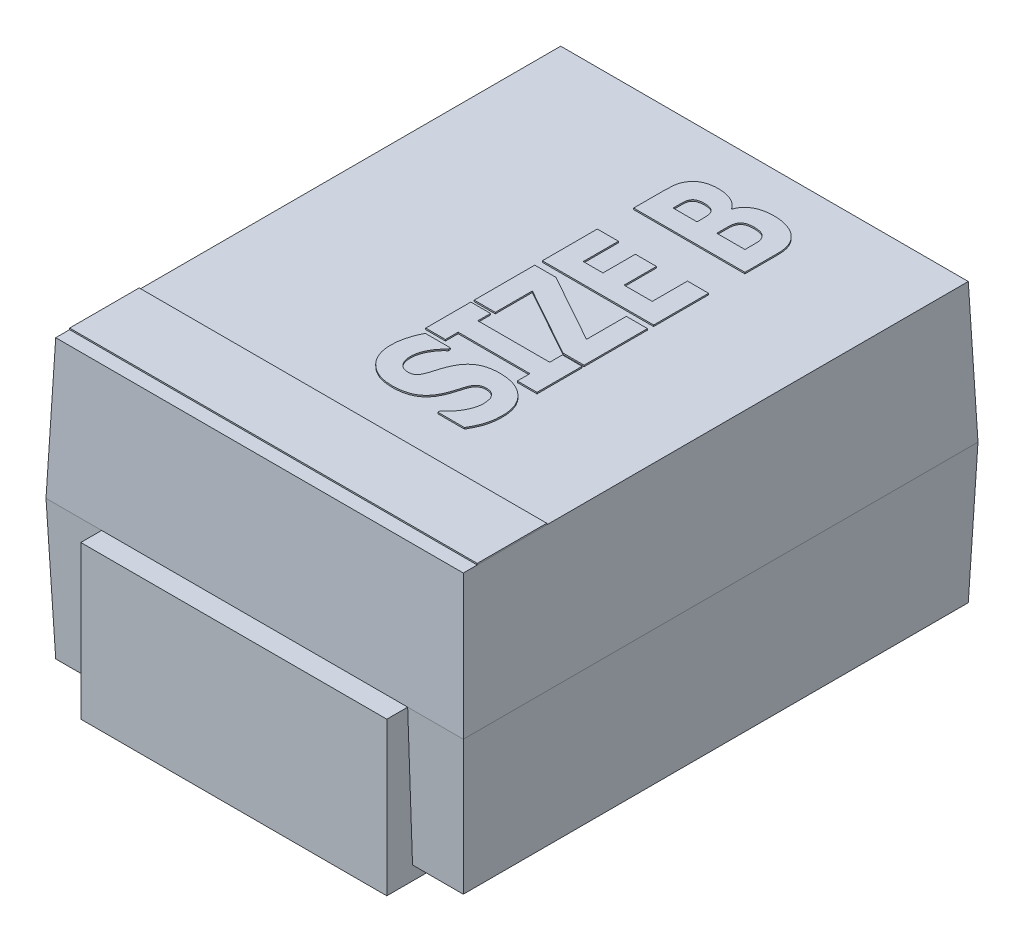
SolidWorks part; units mm, degrees
ref_plane "Front Plane" through (0, 0, 0) normal (0, 0, 1) x (1, 0, 0)
ref_plane "Top Plane" through (0, 0, 0) normal (0, 1, 0) x (1, 0, 0)
ref_plane "Right Plane" through (0, 0, 0) normal (1, 0, 0) x (0, 0, -1)
sketch "Sketch1" plane through (0, 0, 0) normal (0, 1, 0) x (1, 0, 0)
  line L1 (-1.5, 1.85) -> (1.5, 1.85)
  line L2 (-1.5, 1.85) -> (-1.5, -1.85)
  line L3 (-1.5, -1.85) -> (1.5, -1.85)
  line L4 (1.5, 1.85) -> (1.5, -1.85)
  line L5 (-1.5, 1.85) -> (1.5, -1.85) construction
  line L6 (-1.5, -1.85) -> (1.5, 1.85) construction
  point P0 (0, 0)
  dimension "D1" = 3
  dimension "D2" = 3.7
extrude "Boss-Extrude1" add sketch "Sketch1" along normal mid plane 2 draft 2
sketch "Sketch2" plane through (0, -1, 0) normal (0, -1, 0) x (1, 0, 0)
  line L0 (0, 0) -> (3.8147, 0) construction
  line L1 (-1.1, 2) -> (1.1, 2)
  line L2 (-1.1, 2) -> (-1.1, 0.65)
  line L3 (-1.1, 0.65) -> (1.1, 0.65)
  line L4 (1.1, 2) -> (1.1, 0.65)
  line L5 (-1.1, 2) -> (1.1, 0.65) construction
  line L6 (-1.1, 0.65) -> (1.1, 2) construction
  line L7 (-1.1, -0.65) -> (1.1, -0.65)
  line L8 (1.1, -2) -> (1.1, -0.65)
  line L9 (-1.1, -2) -> (1.1, -2)
  line L10 (-1.1, -2) -> (-1.1, -0.65)
  line L11 (0, 0.65) -> (0, -0.65) construction
  point P0 (0, 1.325)
  dimension "D1" = 2.2
  dimension "D2" = 1.35
  dimension "D3" = 4
extrude "Boss-Extrude2" add sketch "Sketch2" along normal blind 0.1 and the other way blind 1
sketch "Sketch3" plane through (0, 1, 0) normal (0, 1, 0) x (1, 0, 0)
  line L0 (-1.4651, -1.4651) -> (1.4651, -1.4651)
  line L1 (-1.4651, 1.8151) -> (-1.4651, -1.8151) construction
  line L2 (1.4651, -1.8151) -> (1.4651, 1.8151) construction
  line L3 (-1.4651, -1.8151) -> (1.4651, -1.8151) construction
  dimension "D1" = 0.35
extrude "Extrude-Thin1" add sketch "Sketch3" along normal blind 0.01 thin thin type mid plane wall 0.5
sketch "Sketch4" plane through (0, 1, 0) normal (0, 1, 0) x (1, 0, 0)
  line L0 (0.6151, -1.2151) -> (0.6151, 1.8151) construction
  line L1 (1.4651, 1.8151) -> (-1.4651, 1.8151) construction
  line L2 (1.4651, -1.2151) -> (1.4651, 1.8151) construction
  line L3 (-1.4651, -1.2151) -> (1.4651, -1.2151) construction
  text T0 "SIZE B" font "Verdana" height 0.8
  dimension "D1" = 0.85
extrude "Boss-Extrude3" add sketch "Sketch4" along normal blind 0.01
